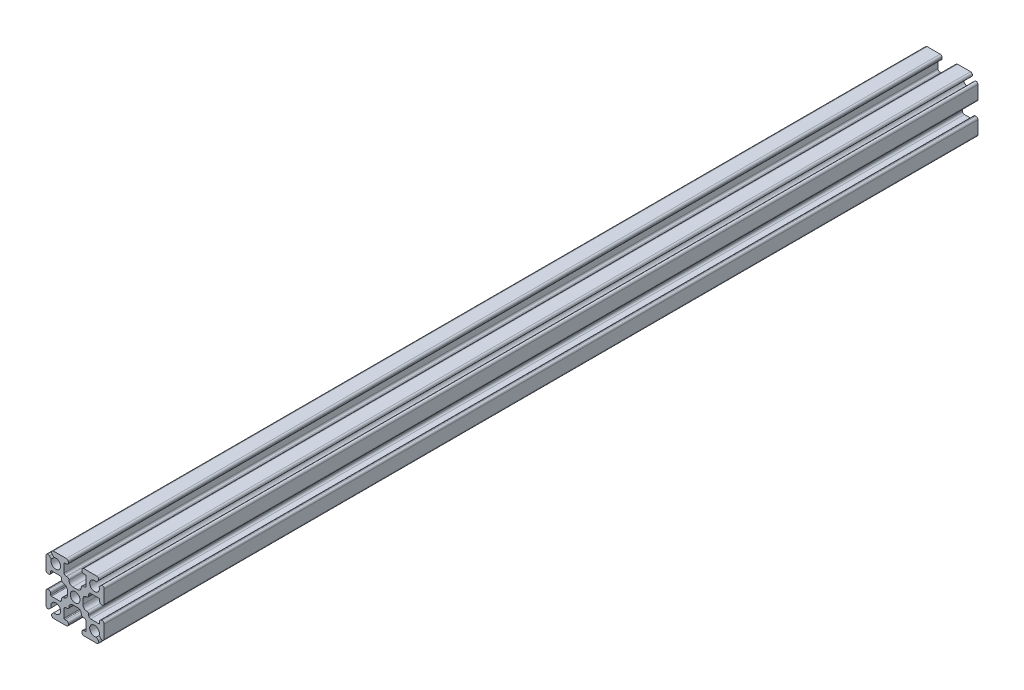
SolidWorks part; units mm, degrees
ref_plane "Front Plane" through (0, 0, 0) normal (0, 0, 1) x (1, 0, 0)
ref_plane "Top Plane" through (0, 0, 0) normal (0, 1, 0) x (1, 0, 0)
ref_plane "Right Plane" through (0, 0, 0) normal (1, 0, 0) x (0, 0, -1)
ref_plane "Plane1" through (0, 0, 225) normal (0, 0, 1) x (1, 0, 0)
sketch "Sketch1" plane through (0, 0, 225) normal (0, 0, 1) x (1, 0, 0)
  line L0 (-5.9393, 6.6464) -> (-5.4565, 6.1636)
  line L1 (-6.1636, 5.4565) -> (-6.6464, 5.9393)
  line L2 (-7.5, 5.5858) -> (-7.5, 2.25)
  line L3 (-7, 1.75) -> (-6.8, 1.75)
  line L4 (-6.3, 2.25) -> (-6.3, 2.65)
  line L5 (-6.1, 2.85) -> (-4, 2.85)
  line L6 (-3.5, 2.35) -> (-3.5, 2.1)
  line L7 (-2, 0.6) -> (-2, -0.6)
  line L8 (-3.5, -2.1) -> (-3.5, -2.35)
  line L9 (-4, -2.85) -> (-6.1, -2.85)
  line L10 (-6.3, -2.65) -> (-6.3, -2.25)
  line L11 (-6.8, -1.75) -> (-7, -1.75)
  line L12 (-7.5, -2.25) -> (-7.5, -5.5858)
  line L13 (-6.6464, -5.9393) -> (-6.1636, -5.4565)
  line L14 (-5.4565, -6.1636) -> (-5.9393, -6.6464)
  line L15 (-5.5858, -7.5) -> (-2.25, -7.5)
  line L16 (-1.75, -7) -> (-1.75, -6.8)
  line L17 (-2.25, -6.3) -> (-2.65, -6.3)
  line L18 (-2.85, -6.1) -> (-2.85, -4)
  line L19 (-2.35, -3.5) -> (-2.1, -3.5)
  line L20 (-0.6, -2) -> (0.6, -2)
  line L21 (2.1, -3.5) -> (2.35, -3.5)
  line L22 (2.85, -4) -> (2.85, -6.1)
  line L23 (2.65, -6.3) -> (2.25, -6.3)
  line L24 (1.75, -6.8) -> (1.75, -7)
  line L25 (2.25, -7.5) -> (5.5858, -7.5)
  line L26 (5.9393, -6.6464) -> (5.4565, -6.1636)
  line L27 (6.1636, -5.4565) -> (6.6464, -5.9393)
  line L28 (7.5, -5.5858) -> (7.5, -2.25)
  line L29 (7, -1.75) -> (6.8, -1.75)
  line L30 (6.3, -2.25) -> (6.3, -2.65)
  line L31 (6.1, -2.85) -> (4, -2.85)
  line L32 (3.5, -2.35) -> (3.5, -2.1)
  line L33 (2, -0.6) -> (2, 0.6)
  line L34 (3.5, 2.1) -> (3.5, 2.35)
  line L35 (4, 2.85) -> (6.1, 2.85)
  line L36 (6.3, 2.65) -> (6.3, 2.25)
  line L37 (6.8, 1.75) -> (7, 1.75)
  line L38 (7.5, 2.25) -> (7.5, 5.5858)
  line L39 (6.6464, 5.9393) -> (6.1636, 5.4565)
  line L40 (5.4565, 6.1636) -> (5.9393, 6.6464)
  line L41 (5.5858, 7.5) -> (2.25, 7.5)
  line L42 (1.75, 7) -> (1.75, 6.8)
  line L43 (2.25, 6.3) -> (2.65, 6.3)
  line L44 (2.85, 6.1) -> (2.85, 4)
  line L45 (2.35, 3.5) -> (2.1, 3.5)
  line L46 (0.6, 2) -> (-0.6, 2)
  line L47 (-2.1, 3.5) -> (-2.35, 3.5)
  line L48 (-2.85, 4) -> (-2.85, 6.1)
  line L49 (-2.65, 6.3) -> (-2.25, 6.3)
  line L50 (-1.75, 6.8) -> (-1.75, 7)
  line L51 (-2.25, 7.5) -> (-5.5858, 7.5)
  circle A0 centre (0, 0) radius 1.25
  arc A1 (-5.5858, 7.5) -> (-5.9393, 6.6464) centre (-5.5858, 7) ccw
  arc A2 (-5.4565, 6.1636) -> (-6.1636, 5.4565) centre (-5, 5) cw
  arc A3 (-6.6464, 5.9393) -> (-7.5, 5.5858) centre (-7, 5.5858) ccw
  arc A4 (-7.5, 2.25) -> (-7, 1.75) centre (-7, 2.25) ccw
  arc A5 (-6.8, 1.75) -> (-6.3, 2.25) centre (-6.8, 2.25) ccw
  arc A6 (-6.3, 2.65) -> (-6.1, 2.85) centre (-6.1, 2.65) cw
  arc A7 (-4, 2.85) -> (-3.5, 2.35) centre (-4, 2.35) cw
  arc A8 (-3.5, 2.1) -> (-3, 1.6) centre (-3, 2.1) ccw
  arc A9 (-3, 1.6) -> (-2, 0.6) centre (-3, 0.6) cw
  arc A10 (-2, -0.6) -> (-3, -1.6) centre (-3, -0.6) cw
  arc A11 (-3, -1.6) -> (-3.5, -2.1) centre (-3, -2.1) ccw
  arc A12 (-3.5, -2.35) -> (-4, -2.85) centre (-4, -2.35) cw
  arc A13 (-6.1, -2.85) -> (-6.3, -2.65) centre (-6.1, -2.65) cw
  arc A14 (-6.3, -2.25) -> (-6.8, -1.75) centre (-6.8, -2.25) ccw
  arc A15 (-7, -1.75) -> (-7.5, -2.25) centre (-7, -2.25) ccw
  arc A16 (-7.5, -5.5858) -> (-6.6464, -5.9393) centre (-7, -5.5858) ccw
  arc A17 (-6.1636, -5.4565) -> (-5.4565, -6.1636) centre (-5, -5) cw
  arc A18 (-5.9393, -6.6464) -> (-5.5858, -7.5) centre (-5.5858, -7) ccw
  arc A19 (-2.25, -7.5) -> (-1.75, -7) centre (-2.25, -7) ccw
  arc A20 (-1.75, -6.8) -> (-2.25, -6.3) centre (-2.25, -6.8) ccw
  arc A21 (-2.65, -6.3) -> (-2.85, -6.1) centre (-2.65, -6.1) cw
  arc A22 (-2.85, -4) -> (-2.35, -3.5) centre (-2.35, -4) cw
  arc A23 (-2.1, -3.5) -> (-1.6, -3) centre (-2.1, -3) ccw
  arc A24 (-1.6, -3) -> (-0.6, -2) centre (-0.6, -3) cw
  arc A25 (0.6, -2) -> (1.6, -3) centre (0.6, -3) cw
  arc A26 (1.6, -3) -> (2.1, -3.5) centre (2.1, -3) ccw
  arc A27 (2.35, -3.5) -> (2.85, -4) centre (2.35, -4) cw
  arc A28 (2.85, -6.1) -> (2.65, -6.3) centre (2.65, -6.1) cw
  arc A29 (2.25, -6.3) -> (1.75, -6.8) centre (2.25, -6.8) ccw
  arc A30 (1.75, -7) -> (2.25, -7.5) centre (2.25, -7) ccw
  arc A31 (5.5858, -7.5) -> (5.9393, -6.6464) centre (5.5858, -7) ccw
  arc A32 (5.4565, -6.1636) -> (6.1636, -5.4565) centre (5, -5) cw
  arc A33 (6.6464, -5.9393) -> (7.5, -5.5858) centre (7, -5.5858) ccw
  arc A34 (7.5, -2.25) -> (7, -1.75) centre (7, -2.25) ccw
  arc A35 (6.8, -1.75) -> (6.3, -2.25) centre (6.8, -2.25) ccw
  arc A36 (6.3, -2.65) -> (6.1, -2.85) centre (6.1, -2.65) cw
  arc A37 (4, -2.85) -> (3.5, -2.35) centre (4, -2.35) cw
  arc A38 (3.5, -2.1) -> (3, -1.6) centre (3, -2.1) ccw
  arc A39 (3, -1.6) -> (2, -0.6) centre (3, -0.6) cw
  arc A40 (2, 0.6) -> (3, 1.6) centre (3, 0.6) cw
  arc A41 (3, 1.6) -> (3.5, 2.1) centre (3, 2.1) ccw
  arc A42 (3.5, 2.35) -> (4, 2.85) centre (4, 2.35) cw
  arc A43 (6.1, 2.85) -> (6.3, 2.65) centre (6.1, 2.65) cw
  arc A44 (6.3, 2.25) -> (6.8, 1.75) centre (6.8, 2.25) ccw
  arc A45 (7, 1.75) -> (7.5, 2.25) centre (7, 2.25) ccw
  arc A46 (7.5, 5.5858) -> (6.6464, 5.9393) centre (7, 5.5858) ccw
  arc A47 (6.1636, 5.4565) -> (5.4565, 6.1636) centre (5, 5) cw
  arc A48 (5.9393, 6.6464) -> (5.5858, 7.5) centre (5.5858, 7) ccw
  arc A49 (2.25, 7.5) -> (1.75, 7) centre (2.25, 7) ccw
  arc A50 (1.75, 6.8) -> (2.25, 6.3) centre (2.25, 6.8) ccw
  arc A51 (2.65, 6.3) -> (2.85, 6.1) centre (2.65, 6.1) cw
  arc A52 (2.85, 4) -> (2.35, 3.5) centre (2.35, 4) cw
  arc A53 (2.1, 3.5) -> (1.6, 3) centre (2.1, 3) ccw
  arc A54 (1.6, 3) -> (0.6, 2) centre (0.6, 3) cw
  arc A55 (-0.6, 2) -> (-1.6, 3) centre (-0.6, 3) cw
  arc A56 (-1.6, 3) -> (-2.1, 3.5) centre (-2.1, 3) ccw
  arc A57 (-2.35, 3.5) -> (-2.85, 4) centre (-2.35, 4) cw
  arc A58 (-2.85, 6.1) -> (-2.65, 6.3) centre (-2.65, 6.1) cw
  arc A59 (-2.25, 6.3) -> (-1.75, 6.8) centre (-2.25, 6.8) ccw
  arc A60 (-1.75, 7) -> (-2.25, 7.5) centre (-2.25, 7) ccw
extrude "Boss-Extrude1" add sketch "Sketch1" against normal blind 225
